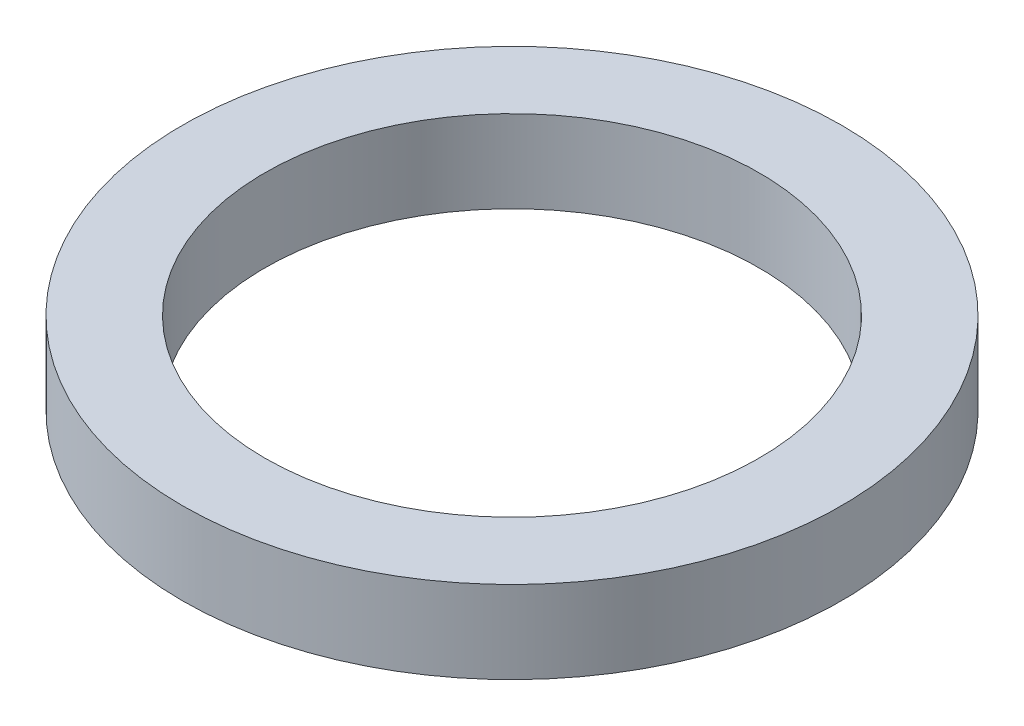
SolidWorks part; units mm, degrees
material "1060 Alloy"
ref_plane "Front Plane" through (0, 0, 0) normal (0, 0, 1) x (1, 0, 0)
ref_plane "Top Plane" through (0, 0, 0) normal (0, 1, 0) x (1, 0, 0)
ref_plane "Right Plane" through (0, 0, 0) normal (1, 0, 0) x (0, 0, -1)
sketch "Sketch1" plane through (0, 0, 0) normal (0, 1, 0) x (1, 0, 0)
  circle A0 centre (0, 0) radius 12
  circle A1 centre (0, 0) radius 16
  dimension "D1" = 24
  dimension "D2" = 4
extrude "Boss-Extrude1" add sketch "Sketch1" along normal blind 4
